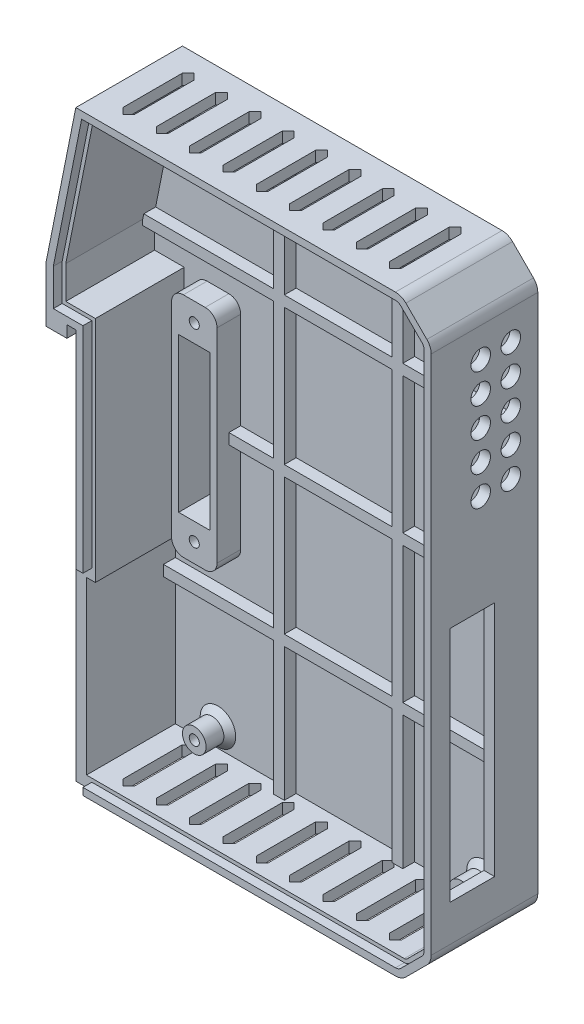
SolidWorks part; units mm, degrees
material "ABS"
ref_plane "Front" through (0, 0, 0) normal (0, 0, 1) x (1, 0, 0)
ref_plane "Top" through (0, 0, 0) normal (0, 1, 0) x (1, 0, 0)
ref_plane "Right" through (0, 0, 0) normal (1, 0, 0) x (0, 0, -1)
sketch "Sketch2" plane through (0, 0, 0) normal (0, 0, 1) x (1, 0, 0)
  line L0 (0, 0) -> (58.9645, 0)
  line L1 (60.7322, 0.7322) -> (64.2678, 4.2678)
  line L2 (65, 6.0355) -> (65, 93.9645)
  line L3 (60.7322, 99.2678) -> (64.2678, 95.7322)
  line L4 (58.9645, 100) -> (5, 100)
  line L5 (5, 100) -> (0, 75)
  line L6 (0, 75) -> (0, 65.5)
  line L7 (0, 65.5) -> (3.5, 65.5)
  line L8 (3.5, 65.5) -> (3.5, 67.5)
  line L9 (3.5, 67.5) -> (5, 67.5)
  line L10 (5, 67.5) -> (5, 32.5)
  line L11 (5, 32.5) -> (0, 32.5)
  line L12 (0, 32.5) -> (0, 0)
  arc A0 (60.7322, 99.2678) -> (58.9645, 100) centre (58.9645, 97.5) ccw
  arc A1 (65, 93.9645) -> (64.2678, 95.7322) centre (62.5, 93.9645) ccw
  arc A2 (64.2678, 4.2678) -> (65, 6.0355) centre (62.5, 6.0355) ccw
  arc A3 (58.9645, 0) -> (60.7322, 0.7322) centre (58.9645, 2.5) ccw
  point P17 (60, 100)
  point P20 (65, 95)
  point P23 (65, 5)
  point P26 (60, 0)
  dimension "D13" = 2.5
  dimension "D1" = 100
  dimension "D2" = 5
  dimension "D3" = 32.5
  dimension "D4" = 5
  dimension "D5" = 35
  dimension "D6" = 1.5
  dimension "D7" = 2
  dimension "D8" = 9.5
  dimension "D9" = 65
  dimension "D10" = 5
  dimension "D11" = 5
  dimension "D12" = 5
extrude "Boss-Extrude1" add sketch "Sketch2" along normal blind 1.5
sketch "Sketch3" plane through (0, 0, 1.5) normal (0, 0, 1) x (1, 0, 0)
  line L0 (5, 32.5) -> (3.5, 32.5)
  line L1 (0, 0) -> (58.9645, 0) construction
  line L2 (3.5, 0) -> (58.9645, 0)
  line L3 (60.7322, 0.7322) -> (64.2678, 4.2678)
  line L4 (65, 6.0355) -> (65, 93.9645)
  line L5 (64.2678, 95.7322) -> (60.7322, 99.2678)
  line L6 (58.9645, 100) -> (5, 100)
  line L7 (5, 100) -> (0, 75)
  line L8 (0, 75) -> (0, 65.5)
  line L9 (0, 65.5) -> (3.5, 65.5)
  line L10 (3.5, 65.5) -> (3.5, 67.5)
  line L11 (3.5, 67.5) -> (5, 67.5)
  line L12 (5, 67.5) -> (5, 32.5)
  line L13 (6.8, 69.3) -> (6.8, 30.7)
  line L14 (6.8, 30.7) -> (5.3, 30.7)
  line L15 (5.3, 30.7) -> (5.3, 1.8)
  line L16 (5.3, 1.8) -> (58.9645, 1.8)
  line L17 (59.4594, 2.005) -> (62.995, 5.5406)
  line L18 (63.2, 6.0355) -> (63.2, 93.9645)
  line L19 (62.995, 94.4594) -> (59.4594, 97.995)
  line L20 (58.9645, 98.2) -> (6.4756, 98.2)
  line L21 (6.4756, 98.2) -> (1.8, 74.8218)
  line L22 (1.8, 74.8218) -> (1.8, 69.3)
  line L23 (1.8, 69.3) -> (1.8, 69.3)
  line L24 (1.8, 69.3) -> (1.8, 69.3)
  line L25 (1.8, 69.3) -> (6.8, 69.3)
  line L26 (5, 32.5) -> (0, 32.5) construction
  line L27 (3.5, 32.5) -> (3.5, 0)
  arc A0 (58.9645, 0) -> (60.7322, 0.7322) centre (58.9645, 2.5) ccw
  arc A1 (64.2678, 4.2678) -> (65, 6.0355) centre (62.5, 6.0355) ccw
  arc A2 (64.2678, 4.2678) -> (65, 6.0355) centre (62.5, 6.0355) ccw construction
  arc A3 (65, 93.9645) -> (64.2678, 95.7322) centre (62.5, 93.9645) ccw
  arc A4 (60.7322, 99.2678) -> (58.9645, 100) centre (58.9645, 97.5) ccw
  arc A5 (58.9645, 1.8) -> (59.4594, 2.005) centre (58.9645, 2.5) ccw
  arc A6 (62.995, 5.5406) -> (63.2, 6.0355) centre (62.5, 6.0355) ccw
  arc A7 (63.2, 93.9645) -> (62.995, 94.4594) centre (62.5, 93.9645) ccw
  arc A8 (59.4594, 97.995) -> (58.9645, 98.2) centre (58.9645, 97.5) ccw
  point P1 (5.385, 1.8933)
  point P59 (-256.6048, 0)
  point P65 (0, 0)
  point P67 (8.2027, 0)
  point P68 (0, 0)
  point P69 (6.8, 1.8)
  point P70 (5.8802, 1.8)
  point P71 (5.7086, 1.8)
  point P72 (3.5818, 0)
  point P73 (0, 0)
  dimension "D3" = 1.5
  dimension "D1" = 1.8
extrude "Boss-Extrude2" add sketch "Sketch3" along normal blind 16.5
sketch "Sketch4" plane through (0, 0, 1.5) normal (0, 0, 1) x (1, 0, 0)
  line L1 (10.66, 30.8) -> (14.34, 30.8)
  line L2 (8.66, 32.8) -> (8.66, 67.2)
  line L3 (10.66, 69.2) -> (14.34, 69.2)
  line L4 (16.34, 32.8) -> (16.34, 67.2)
  line L5 (8.66, 30.8) -> (16.34, 69.2) construction
  line L6 (8.66, 69.2) -> (16.34, 30.8) construction
  line L12 (6.8, 69.3) -> (6.8, 30.7) construction
  line L13 (5.3, 1.8) -> (58.9645, 1.8) construction
  arc A0 (10.66, 30.8) -> (8.66, 32.8) centre (10.66, 32.8) cw
  arc A1 (14.34, 30.8) -> (16.34, 32.8) centre (14.34, 32.8) ccw
  arc A2 (14.34, 69.2) -> (16.34, 67.2) centre (14.34, 67.2) cw
  arc A3 (8.66, 67.2) -> (10.66, 69.2) centre (10.66, 67.2) cw
  point P0 (12.5, 50)
  point P21 (12.5, 50)
  point P24 (-1.2056, 39.7622)
  dimension "D2" = 2
  dimension "D1" = 29
  dimension "D3" = 7.68
  dimension "D4" = 38.4
  dimension "D5" = 1.86
extrude "Boss-Extrude3" add sketch "Sketch4" along normal blind 4
sketch "Sketch5" plane through (0, 0, 1.5) normal (0, 0, 1) x (1, 0, 0)
  line L0 (1.9756, 75.7) -> (23.9, 75.7)
  line L2 (23.9, 75.7) -> (23.9, 98.2)
  line L4 (23.9, 98.2) -> (25.7, 98.2)
  line L5 (25.7, 98.2) -> (25.7, 75.7)
  line L6 (25.7, 75.7) -> (43.9, 75.7)
  line L7 (43.9, 75.7) -> (43.9, 98.2)
  line L9 (43.9, 98.2) -> (45.7, 98.2)
  line L10 (45.7, 98.2) -> (45.7, 75.7)
  line L11 (45.7, 75.7) -> (63.2, 75.7)
  line L13 (63.2, 75.7) -> (63.2, 73.9)
  line L14 (63.2, 73.9) -> (45.7, 73.9)
  line L15 (45.7, 73.9) -> (45.7, 50.9)
  line L16 (45.7, 50.9) -> (63.2, 50.9)
  line L17 (63.2, 50.9) -> (63.2, 49.1)
  line L18 (63.2, 49.1) -> (45.7, 49.1)
  line L19 (45.7, 49.1) -> (45.7, 26.1)
  line L20 (45.7, 26.1) -> (63.2, 26.1)
  line L21 (63.2, 26.1) -> (63.2, 24.3)
  line L22 (63.2, 24.3) -> (45.7, 24.3)
  line L23 (45.7, 24.3) -> (45.7, 1.8)
  line L25 (45.7, 1.8) -> (43.9, 1.8)
  line L26 (43.9, 1.8) -> (43.9, 24.3)
  line L27 (43.9, 24.3) -> (25.7, 24.3)
  line L28 (25.7, 24.3) -> (25.7, 1.8)
  line L29 (23.9, 1.8) -> (23.9, 24.3)
  line L31 (23.9, 24.3) -> (5.3, 24.3)
  line L32 (5.3, 24.3) -> (5.3, 26.1)
  line L33 (5.3, 26.1) -> (23.9, 26.1)
  line L34 (23.9, 26.1) -> (23.9, 49.1)
  line L35 (23.9, 49.1) -> (16.34, 49.1)
  line L36 (16.34, 32.8) -> (16.34, 67.2) construction
  line L37 (16.34, 49.1) -> (16.34, 50.9)
  line L38 (16.34, 50.9) -> (23.9, 50.9)
  line L39 (23.9, 50.9) -> (23.9, 73.9)
  line L40 (23.9, 73.9) -> (1.8, 73.9)
  line L42 (1.8, 73.9) -> (1.8, 74.8218)
  line L43 (1.8, 74.8218) -> (1.9756, 75.7)
  line L44 (23.9, 1.8) -> (25.7, 1.8)
  line L45 (25.7, 73.9) -> (43.9, 73.9)
  line L46 (25.7, 73.9) -> (25.7, 50.9)
  line L47 (25.7, 50.9) -> (43.9, 50.9)
  line L48 (43.9, 73.9) -> (43.9, 50.9)
  line L49 (25.7, 49.1) -> (43.9, 49.1)
  line L50 (25.7, 49.1) -> (25.7, 26.1)
  line L51 (25.7, 26.1) -> (43.9, 26.1)
  line L52 (43.9, 49.1) -> (43.9, 26.1)
  line L55 (5.3, 30.7) -> (5.3, 1.8) construction
  line L56 (63.2, 6.0355) -> (63.2, 93.9645) construction
  line L57 (63.2, 6.0355) -> (63.2, 93.9645) construction
  line L59 (58.9645, 98.2) -> (6.4756, 98.2) construction
  line L60 (58.9645, 98.2) -> (6.4756, 98.2) construction
  line L61 (1.8, 74.8218) -> (1.8, 69.3) construction
  line L62 (6.4756, 98.2) -> (1.8, 74.8218) construction
  line L63 (5.3, 30.7) -> (5.3, 1.8) construction
  line L64 (5.3, 1.8) -> (58.9645, 1.8) construction
  point P2 (0, 0)
  point P7 (0, 0)
  point P17 (0, 0)
  point P18 (0, 0)
  point P30 (0, 0)
  point P31 (0, 0)
  point P38 (0, 0)
  point P39 (0, 0)
  point P51 (0, 0)
  point P52 (0, 0)
  point P62 (0, 0)
  point P63 (0, 0)
  point P64 (0, 0)
  point P65 (0, 0)
  point P67 (0, 0)
  point P69 (0, 0)
  point P70 (0, 0)
  point P71 (0, 0)
  point P74 (0, 0)
  point P77 (0, 0)
  point P78 (0, 0)
  point P79 (0, 0)
  point P80 (0, 0)
  point P81 (0, 0)
  point P82 (0, 0)
  point P83 (0, 0)
  point P85 (0, 0)
  point P89 (0, 0)
  point P90 (16.34, 48.904)
  point P91 (0, 0)
  point P94 (0, 0)
  dimension "D1" = 1.8
  dimension "D2" = 22.5
  dimension "D3" = 23
  dimension "D4" = 23
  dimension "D5" = 22.5
  dimension "D6" = 18.6
  dimension "D7" = 18.2
  dimension "D8" = 17.5
extrude "Boss-Extrude4" add sketch "Sketch5" along normal blind 2
sketch "Sketch6" plane through (0, 0, 1.5) normal (0, 0, 1) x (1, 0, 0)
  line L0 (12.5, 95) -> (57.5, 95) construction
  line L1 (57.5, 95) -> (57.5, 5) construction
  line L2 (57.5, 5) -> (12.5, 5) construction
  line L3 (12.5, 5) -> (12.5, 95) construction
  circle A0 centre (12.5, 5) radius 2
  circle A1 centre (57.5, 5) radius 2
  circle A2 centre (12.5, 95) radius 2
  circle A3 centre (57.5, 95) radius 2
  point P10 (14.1216, 93.1321)
  dimension "D3" = 4
  dimension "D4" = 12.5
  dimension "D1" = 45
  dimension "D2" = 90
  dimension "D5" = 95
extrude "Boss-Extrude5" add sketch "Sketch6" along normal blind 4
chamfer "Chamfer1" distance 1 angle 45 4 edges at (14.5, 5, 1.5) (59.5, 5, 1.5) (59.5, 95, 1.5) (14.5, 95, 1.5)
sketch "Sketch7" plane through (0, 0, 1.5) normal (0, 0, 1) x (1, 0, 0)
  line L1 (0, 32.5) -> (3.5, 32.5)
  line L2 (0, 32.5) -> (0, 0)
  line L3 (0, 0) -> (3.5, 0)
  line L4 (3.5, 32.5) -> (3.5, 0)
extrude "Cut-Extrude1" cut sketch "Sketch7" against normal blind 0.5
sketch "Sketch8" plane through (0, 0, 1) normal (0, 0, 1) x (1, 0, 0)
  line L1 (0, 0) -> (1.4, 0)
  line L2 (0, 0) -> (0, 21)
  line L3 (0, 21) -> (1.4, 21)
  line L4 (1.4, 0) -> (1.4, 21)
  dimension "D1" = 1.4
  dimension "D2" = 21
extrude "Boss-Extrude6" add sketch "Sketch8" along normal blind 2.9
sketch "Sketch9" plane through (0, 0, 5.5) normal (0, 0, 1) x (1, 0, 0)
  circle A0 centre (12.5, 95) radius 0.85
  circle A1 centre (57.5, 95) radius 0.85
  circle A2 centre (57.5, 5) radius 0.85
  circle A3 centre (12.5, 5) radius 0.85
  circle A4 centre (12.5, 95) radius 2 construction
  point P14 (12.5, 95)
  dimension "D1" = 1.7
extrude "Cut-Extrude2" cut sketch "Sketch9" against normal blind 4
sketch "Sketch10" plane through (0, 0, 5.5) normal (0, 0, 1) x (1, 0, 0)
  line L0 (12.5, 69.2) -> (12.5, 30.8) construction
  line L1 (9.86, 37) -> (15.14, 37)
  line L2 (9.86, 37) -> (9.86, 63)
  line L3 (9.86, 63) -> (15.14, 63)
  line L4 (15.14, 37) -> (15.14, 63)
  line L5 (9.86, 37) -> (15.14, 63) construction
  line L6 (9.86, 63) -> (15.14, 37) construction
  line L7 (14.34, 69.2) -> (10.66, 69.2) construction
  line L8 (10.66, 30.8) -> (14.34, 30.8) construction
  point P0 (12.5, 50)
  point P11 (0, 0)
  dimension "D1" = 5.28
  dimension "D2" = 26
extrude "Cut-Extrude3" cut sketch "Sketch10" against normal through all
sketch "Sketch11" plane through (0, 0, 5.5) normal (0, 0, 1) x (1, 0, 0)
  line L0 (12.5, 69.2) -> (12.5, 30.8) construction
  line L1 (14.34, 69.2) -> (10.66, 69.2) construction
  line L2 (10.66, 30.8) -> (14.34, 30.8) construction
  line L3 (8.66, 50) -> (16.34, 50) construction
  line L4 (8.66, 67.2) -> (8.66, 32.8) construction
  line L5 (16.34, 32.8) -> (16.34, 67.2) construction
  circle A0 centre (12.5, 66) radius 0.85
  circle A1 centre (12.5, 34) radius 0.85
  point P16 (0, 0)
  dimension "D1" = 1.7
  dimension "D2" = 32
extrude "Cut-Extrude4" cut sketch "Sketch11" against normal blind 4
sketch "Sketch12" plane through (3.5, 0, 0) normal (-1, 0, 0) x (0, 0, 1)
  line L0 (0, 16.65) -> (9, 16.65) construction
  line L1 (7.75, 17.9) -> (10.25, 17.9)
  line L2 (7.75, 17.9) -> (7.75, 15.4)
  line L3 (7.75, 15.4) -> (10.25, 15.4)
  line L4 (10.25, 17.9) -> (10.25, 15.4)
  line L5 (7.75, 17.9) -> (10.25, 15.4) construction
  line L6 (7.75, 15.4) -> (10.25, 17.9) construction
  line L7 (0, 32.5) -> (0, 0) construction
  line L8 (9, 16.65) -> (18, 16.65) construction
  line L9 (18, 32.5) -> (18, 0) construction
  point P0 (9, 16.65)
  point P12 (0, 0)
  dimension "D1" = 2.5
  dimension "D2" = 7.75
  dimension "D3" = 16.65
  dimension "D4" = 15.4
ref_plane "Plane1" through (2.5, 0, 0) normal (-1, 0, 0) x (0, 0, 1)
sketch "Sketch13" plane through (2.5, 0, 0) normal (-1, 0, 0) x (0, 0, 1)
  line L0 (7.75, 15.4) -> (10.25, 17.9) construction
  line L1 (8.75, 16.4) -> (9.25, 16.4)
  line L2 (8.75, 16.4) -> (8.75, 16.9)
  line L3 (8.75, 16.9) -> (9.25, 16.9)
  line L4 (9.25, 16.4) -> (9.25, 16.9)
  line L5 (8.75, 16.4) -> (9.25, 16.9) construction
  line L6 (8.75, 16.9) -> (9.25, 16.4) construction
  point P0 (9, 16.65)
  dimension "D1" = 0.5
loft "Loft2" add profiles "Sketch12", "Sketch13"
sketch "Sketch14" plane through (0, 0, 18) normal (0, 0, 1) x (1, 0, 0)
  line L0 (1.8, 69.3) -> (1.8, 74.8218)
  line L1 (1.8, 74.8218) -> (6.4756, 98.2)
  line L2 (6.4756, 98.2) -> (58.9645, 98.2)
  line L3 (59.4594, 97.995) -> (62.995, 94.4594)
  line L4 (63.2, 93.9645) -> (63.2, 6.0355)
  line L5 (63.2, 6.0355) -> (63.2, 24.3) construction
  line L6 (62.995, 5.5406) -> (59.4594, 2.005)
  line L7 (58.9645, 1.8) -> (5.3, 1.8)
  line L8 (5.3, 1.8) -> (5.3, 30.7)
  line L9 (5.3, 30.7) -> (6.8, 30.7)
  line L10 (6.8, 30.7) -> (6.8, 69.3)
  line L11 (6.8, 69.3) -> (1.8, 69.3)
  line L12 (1.2, 74.8812) -> (5.9838, 98.8)
  line L13 (5.9838, 98.8) -> (58.9645, 98.8)
  line L14 (59.8837, 98.4192) -> (63.4192, 94.8837)
  line L15 (63.8, 93.9645) -> (63.8, 6.0355)
  line L16 (63.4192, 5.1163) -> (59.8837, 1.5808)
  line L17 (58.9645, 1.2) -> (4.7, 1.2)
  line L18 (4.7, 1.2) -> (4.7, 31.3)
  line L19 (4.7, 31.3) -> (6.2, 31.3)
  line L20 (6.2, 31.3) -> (6.2, 68.7)
  line L21 (6.2, 68.7) -> (1.2, 68.7)
  line L22 (1.2, 68.7) -> (1.2, 74.8812)
  arc A0 (58.9645, 98.2) -> (59.4594, 97.995) centre (58.9645, 97.5) cw
  arc A1 (62.995, 94.4594) -> (63.2, 93.9645) centre (62.5, 93.9645) cw
  arc A2 (62.995, 5.5406) -> (63.2, 6.0355) centre (62.5, 6.0355) ccw construction
  arc A3 (63.2, 6.0355) -> (62.995, 5.5406) centre (62.5, 6.0355) cw
  arc A4 (59.4594, 2.005) -> (58.9645, 1.8) centre (58.9645, 2.5) cw
  arc A5 (58.9645, 98.8) -> (59.8837, 98.4192) centre (58.9645, 97.5) cw
  arc A6 (63.4192, 94.8837) -> (63.8, 93.9645) centre (62.5, 93.9645) cw
  arc A7 (63.8, 6.0355) -> (63.4192, 5.1163) centre (62.5, 6.0355) cw
  arc A8 (59.8837, 1.5808) -> (58.9645, 1.2) centre (58.9645, 2.5) cw
  dimension "D1" = 0.6
extrude "Cut-Extrude5" cut sketch "Sketch14" against normal blind 1.5
sketch "Sketch15" plane through (0, 0, 18) normal (0, 0, 1) x (1, 0, 0)
  line L0 (6.2, 68.7) -> (6.2, 31.3) construction
  line L1 (3.5, 0) -> (6.2, 0)
  line L2 (3.5, 0) -> (3.5, 32.5)
  line L3 (3.5, 32.5) -> (6.2, 32.5)
  line L4 (6.2, 0) -> (6.2, 32.5)
  line L5 (6.2, 68.7) -> (6.2, 31.3) construction
  line L6 (5, 32.5) -> (3.5, 32.5) construction
  point P7 (0, 0)
  point P8 (6.2, 31.9352)
  point P11 (0, 0)
extrude "Cut-Extrude6" cut sketch "Sketch15" against normal up to surface (1.5 mm away) up to face at (34.9102, 51.6548, 16.5)
sketch "Sketch16" plane through (0, 0, 0) normal (0, -1, 0) x (1, 0, 0)
  line L0 (8.964, 14) -> (9.964, 15)
  line L1 (9.964, 15) -> (10.964, 14)
  line L2 (10.964, 14) -> (10.964, 4)
  line L3 (10.964, 4) -> (9.964, 3)
  line L4 (9.964, 3) -> (8.964, 4)
  line L5 (8.964, 4) -> (8.964, 14)
  line L6 (0, 0) -> (58.9645, 0) construction
  line L7 (15.594, 3) -> (14.594, 4)
  line L8 (16.594, 4) -> (15.594, 3)
  line L9 (16.594, 14) -> (16.594, 4)
  line L10 (14.594, 4) -> (14.594, 14)
  line L11 (14.594, 14) -> (15.594, 15)
  line L12 (15.594, 15) -> (16.594, 14)
  line L13 (21.224, 3) -> (20.224, 4)
  line L14 (22.224, 4) -> (21.224, 3)
  line L15 (22.224, 14) -> (22.224, 4)
  line L16 (20.224, 4) -> (20.224, 14)
  line L17 (20.224, 14) -> (21.224, 15)
  line L18 (21.224, 15) -> (22.224, 14)
  line L19 (26.854, 3) -> (25.854, 4)
  line L20 (27.854, 4) -> (26.854, 3)
  line L21 (27.854, 14) -> (27.854, 4)
  line L22 (25.854, 4) -> (25.854, 14)
  line L23 (25.854, 14) -> (26.854, 15)
  line L24 (26.854, 15) -> (27.854, 14)
  line L25 (32.484, 3) -> (31.484, 4)
  line L26 (33.484, 4) -> (32.484, 3)
  line L27 (33.484, 14) -> (33.484, 4)
  line L28 (31.484, 4) -> (31.484, 14)
  line L29 (31.484, 14) -> (32.484, 15)
  line L30 (32.484, 15) -> (33.484, 14)
  line L31 (38.114, 3) -> (37.114, 4)
  line L32 (39.114, 4) -> (38.114, 3)
  line L33 (39.114, 14) -> (39.114, 4)
  line L34 (37.114, 4) -> (37.114, 14)
  line L35 (37.114, 14) -> (38.114, 15)
  line L36 (38.114, 15) -> (39.114, 14)
  line L37 (43.744, 3) -> (42.744, 4)
  line L38 (44.744, 4) -> (43.744, 3)
  line L39 (44.744, 14) -> (44.744, 4)
  line L40 (42.744, 4) -> (42.744, 14)
  line L41 (42.744, 14) -> (43.744, 15)
  line L42 (43.744, 15) -> (44.744, 14)
  line L43 (49.374, 3) -> (48.374, 4)
  line L44 (50.374, 4) -> (49.374, 3)
  line L45 (50.374, 14) -> (50.374, 4)
  line L46 (48.374, 4) -> (48.374, 14)
  line L47 (48.374, 14) -> (49.374, 15)
  line L48 (49.374, 15) -> (50.374, 14)
  line L49 (55.004, 3) -> (54.004, 4)
  line L50 (56.004, 4) -> (55.004, 3)
  line L51 (56.004, 14) -> (56.004, 4)
  line L52 (54.004, 4) -> (54.004, 14)
  line L53 (54.004, 14) -> (55.004, 15)
  line L54 (55.004, 15) -> (56.004, 14)
  line L55 (9.964, 3) -> (15.594, 3) construction
  dimension "D1" = 2
  dimension "D2" = 12
  dimension "D3" = 9.964
  dimension "D4" = 3
  dimension "D5" = 135
  dimension "D7" = 5.63
  dimension "D6" = 9
extrude "Cut-Extrude7" cut sketch "Sketch16" against normal blind 1.8
ref_plane "Plane2" through (0, 50, 0) normal (0, -1, 0) x (-1, 0, 0)
mirror "Mirror1" about plane through (0, 50, 0) normal (0, -1, 0) of "Cut-Extrude7"
sketch "Sketch17" plane through (65, 0, 0) normal (1, 0, 0) x (0, 0, -1)
  line L0 (0, 6.0355) -> (0, 93.9645) construction
  line L1 (-7.29, 12.198) -> (-14.807, 12.198)
  line L2 (-7.29, 12.198) -> (-7.29, 52.241)
  line L3 (-7.29, 52.241) -> (-14.807, 52.241)
  line L4 (-14.807, 12.198) -> (-14.807, 52.241)
  point P7 (-11.0485, 12.198)
  dimension "D1" = 7.29
  dimension "D2" = 12.198
  dimension "D3" = 7.517
  dimension "D4" = 40.043
extrude "Cut-Extrude8" cut sketch "Sketch17" against normal blind 1.8
sketch "Sketch18" plane through (65, 0, 0) normal (1, 0, 0) x (0, 0, -1)
  line L0 (0, 6.0355) -> (0, 93.9645) construction
  line L1 (-9.64, 68.969) -> (-4.56, 68.969) construction
  line L2 (-9.64, 68.969) -> (-9.64, 73.969) construction
  circle A0 centre (-9.64, 68.969) radius 1.65
  circle A1 centre (-4.56, 68.969) radius 1.65
  circle A2 centre (-4.56, 73.969) radius 1.65
  circle A3 centre (-4.56, 78.969) radius 1.65
  circle A4 centre (-4.56, 83.969) radius 1.65
  circle A5 centre (-4.56, 88.969) radius 1.65
  circle A6 centre (-9.64, 73.969) radius 1.65
  circle A7 centre (-9.64, 78.969) radius 1.65
  circle A8 centre (-9.64, 83.969) radius 1.65
  circle A9 centre (-9.64, 88.969) radius 1.65
  dimension "D1" = 3.3
  dimension "D2" = 9.64
  dimension "D3" = 68.969
  dimension "D6" = 5.08
  dimension "D7" = 5
  dimension "D4" = 2
  dimension "D5" = 5
extrude "Cut-Extrude9" cut sketch "Sketch18" against normal blind 1.8
